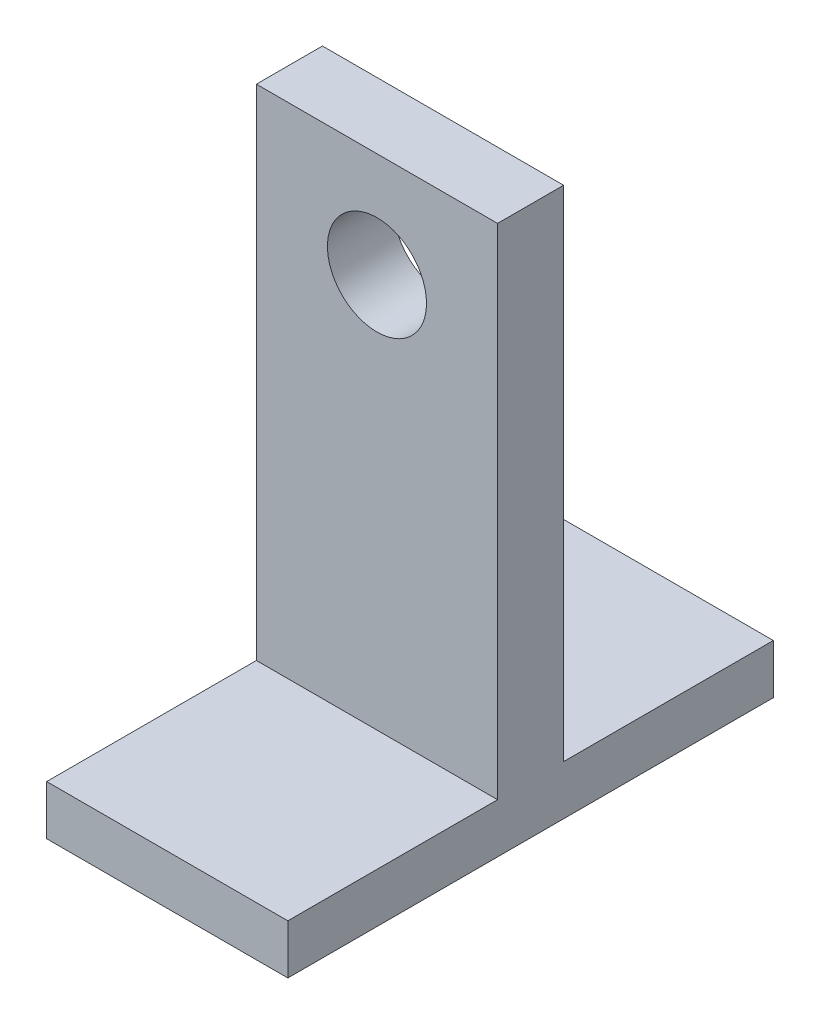
SolidWorks part; units mm, degrees
ref_plane "Front Plane" through (0, 0, 0) normal (0, 0, 1) x (1, 0, 0)
ref_plane "Top Plane" through (0, 0, 0) normal (0, 1, 0) x (1, 0, 0)
ref_plane "Right Plane" through (0, 0, 0) normal (1, 0, 0) x (0, 0, -1)
sketch "Sketch1" plane through (0, 0, 0) normal (1, 0, 0) x (0, 0, -1)
  line L0 (-7.35, 0) -> (7.35, 0)
  line L1 (7.35, 0) -> (7.35, 1.5)
  line L2 (7.35, 1.5) -> (1, 1.5)
  line L3 (1, 1.5) -> (1, 16.613)
  line L4 (1, 16.613) -> (-1, 16.613)
  line L5 (-1, 16.613) -> (-1, 1.5)
  line L6 (-1, 1.5) -> (-7.35, 1.5)
  line L7 (-7.35, 1.5) -> (-7.35, 0)
  line L8 (0, 0) -> (0, 16.613) construction
  dimension "D1" = 1.5
  dimension "D2" = 2
  dimension "D3" = 6.35
  dimension "D4" = 15.113
extrude "Boss-Extrude1" add sketch "Sketch1" along normal mid plane 7.3025
sketch "Sketch3" plane through (0, 0, 1) normal (0, 0, 1) x (1, 0, 0)
  line L0 (-3.6512, 7.088) -> (3.6512, 7.088) construction
  line L1 (-3.6512, 16.613) -> (-3.6512, 1.5) construction
  line L2 (3.6512, 16.613) -> (3.6512, 1.5) construction
  line L3 (3.6512, 1.5) -> (-3.6512, 1.5) construction
  line L4 (0, 13.438) -> (0, 7.088) construction
  circle A0 centre (0, 13.438) radius 1.5
  dimension "D3" = 6.35
  dimension "D1" = 3
  dimension "D2" = 5.588
extrude "Cut-Extrude1" cut sketch "Sketch3" against normal through all
equation "\"wallthickness\"= .118in"
equation "\"floorThickness\"= .220in"
equation "\"D4@Sketch1\"=\"floorThickness\"+.375in"
equation "\"D2@Sketch3\"=\"floorThickness\""
